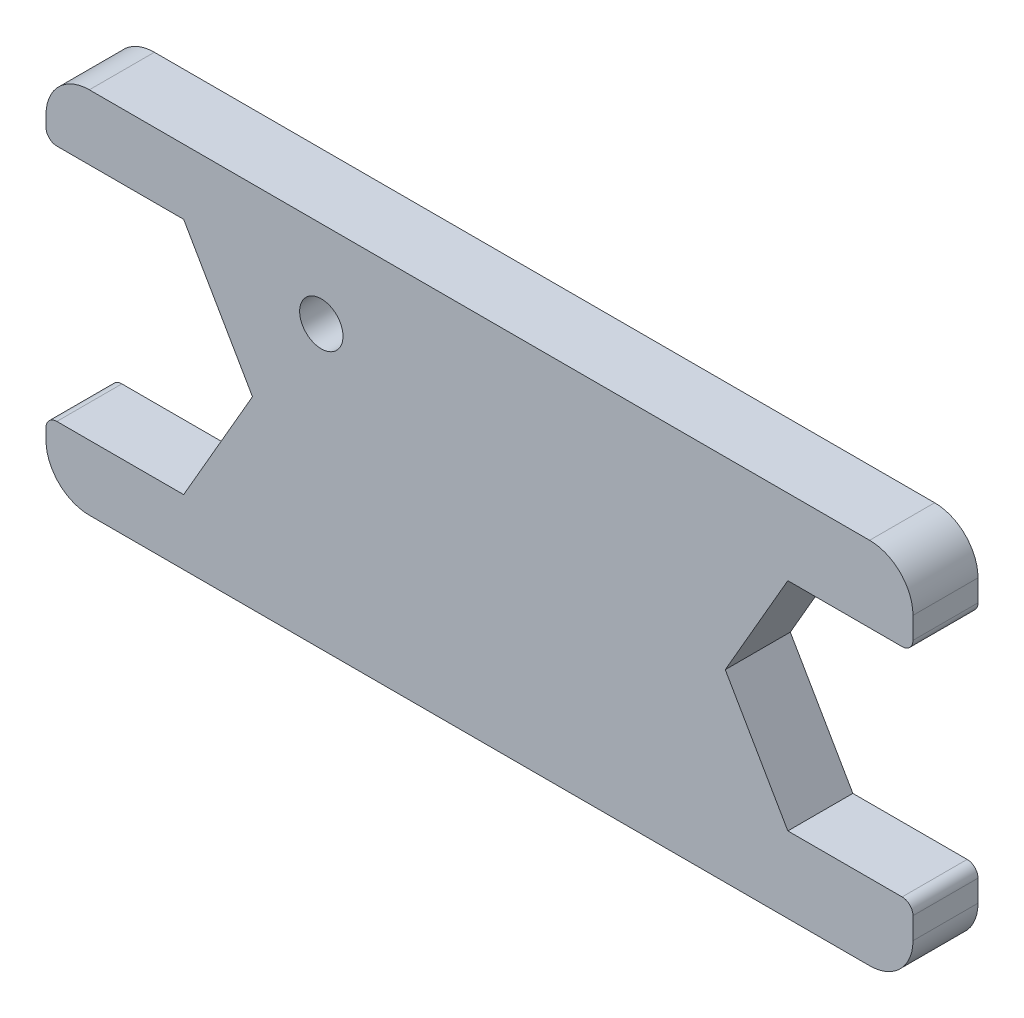
SolidWorks part; units mm, degrees
ref_plane "Front Plane" through (0, 0, 0) normal (0, 0, 1) x (1, 0, 0)
ref_plane "Top Plane" through (0, 0, 0) normal (0, 1, 0) x (1, 0, 0)
ref_plane "Right Plane" through (0, 0, 0) normal (1, 0, 0) x (0, 0, -1)
sketch "Sketch1" plane through (0, 0, 0) normal (0, 0, 1) x (1, 0, 0)
  line L1 (3.1754, 5.5) -> (-3.1754, 5.5)
  line L2 (-3.1754, 5.5) -> (-6.3509, 0)
  line L3 (-6.3509, 0) -> (-3.1754, -5.5)
  line L4 (-3.1754, -5.5) -> (3.1754, -5.5)
  line L5 (3.1754, -5.5) -> (6.3509, 0)
  line L6 (6.3509, 0) -> (3.1754, 5.5)
  line L7 (36.8246, -8.5) -> (-3.1754, -8.5)
  line L8 (36.8246, -8.5) -> (36.8246, 8.5)
  line L9 (36.8246, 8.5) -> (-3.1754, 8.5)
  line L10 (-3.1754, -8.5) -> (-3.1754, 8.5)
  line L11 (36.8246, -8.5) -> (-3.1754, 8.5) construction
  line L12 (36.8246, 8.5) -> (-3.1754, -8.5) construction
  line L13 (36.8246, 5) -> (31.0511, 5)
  line L14 (31.0511, 5) -> (28.1643, 0)
  line L15 (28.1643, 0) -> (31.0511, -5)
  line L16 (31.0511, -5) -> (36.8246, -5)
  line L17 (36.8246, -5) -> (39.7113, 0)
  line L18 (39.7113, 0) -> (36.8246, 5)
  circle A0 centre (0, 0) radius 5.5 construction
  circle A1 centre (33.9378, 0) radius 5 construction
  point P1 (16.8246, 0)
  point P15 (0, 0)
  point P23 (0, 0)
  dimension "D1" = 11
  dimension "D2" = 10
  dimension "D3" = 3
  dimension "D4" = 40
extrude "Boss-Extrude1" add sketch "Sketch1" along normal blind 3 contours L16 L15 L14 L13 L8 L9 L10 L1 L6 L5 L4 L7
fillet "Fillet1" radius 0.5 4 edges at (36.8246, -5, 1.5) (36.8246, 5, 1.5) (-3.1754, -5.5, 1.5) (-3.1754, 5.5, 1.5)
fillet "Fillet2" radius 2 4 edges at (-3.1754, 8.5, 1.5) (-3.1754, -8.5, 1.5) (36.8246, -8.5, 1.5) (36.8246, 8.5, 1.5)
sketch "Sketch2" plane through (0, 0, 3) normal (0, 0, 1) x (1, 0, 0)
  line L0 (6.3509, 0) -> (3.1754, 5.5) construction
  line L1 (34.8246, 8.5) -> (-1.1754, 8.5) construction
  circle A0 centre (9.5263, 4.5) radius 1
  dimension "D1" = 2
  dimension "D2" = 5
  dimension "D3" = 4
extrude "Cut-Extrude1" cut sketch "Sketch2" against normal up to surface (3 mm away) up to face at (16.9164, 0, 0)
